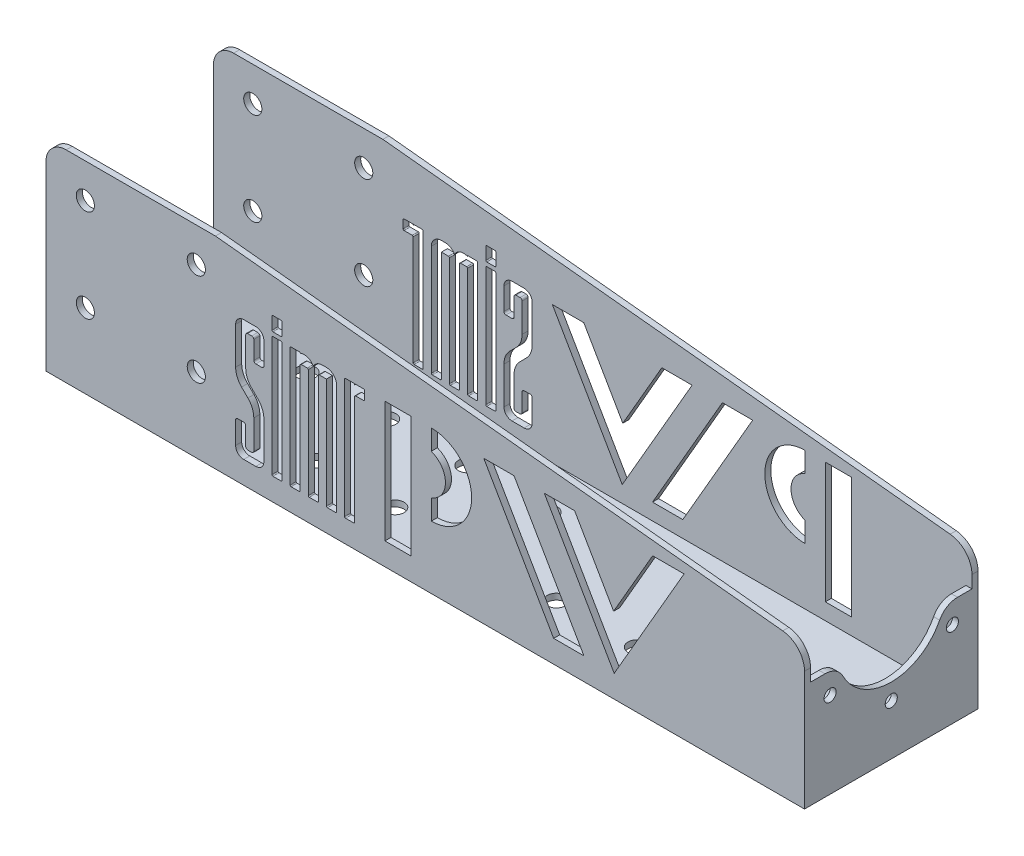
SolidWorks part; units mm, degrees
ref_plane "Płaszczyzna przednia" through (0, 0, 0) normal (0, 0, 1) x (1, 0, 0)
ref_plane "Płaszczyzna górna" through (0, 0, 0) normal (0, 1, 0) x (1, 0, 0)
ref_plane "Płaszczyzna prawa" through (0, 0, 0) normal (1, 0, 0) x (0, 0, -1)
sketch "Szkic1" plane through (0, 0, 0) normal (0, 1, 0) x (1, 0, 0)
  line L1 (-188, -43) -> (188, -43)
  line L2 (-188, -43) -> (-188, 43)
  line L3 (-188, 43) -> (188, 43)
  line L4 (188, -43) -> (188, 43)
  line L5 (-188, -43) -> (188, 43) construction
  line L6 (-188, 43) -> (188, -43) construction
  point P0 (0, 0)
  dimension "D1" = 376
  dimension "D2" = 86
extrude "Dodanie-wyciągnięcie1" add sketch "Szkic1" along normal blind 100
sketch "Szkic2" plane through (188, 0, 0) normal (1, 0, 0) x (0, 0, -1)
  line L0 (-43, 100) -> (43, 100) construction
  line L1 (-40, 100) -> (40, 100)
  line L2 (-40, 100) -> (-40, 3)
  line L3 (-40, 3) -> (40, 3)
  line L4 (40, 100) -> (40, 3)
  line L5 (-43, 100) -> (-43, 0) construction
  line L6 (43, 100) -> (43, 0) construction
  line L7 (-43, 0) -> (43, 0) construction
  dimension "D1" = 3
  dimension "D2" = 3
  dimension "D3" = 3
extrude "Wytnij-wyciągnięcie1" cut sketch "Szkic2" against normal through all
sketch "Szkic3" plane through (0, 0, 43) normal (0, 0, 1) x (1, 0, 0)
  line L0 (-104, 100) -> (188, 70)
  line L1 (-188, 100) -> (188, 100) construction
  line L3 (-188, 100) -> (-188, 0) construction
  line L4 (188, 100) -> (188, 0) construction
  line L5 (-188, 0) -> (188, 0) construction
  line M3 (188, 0) -> (188, 100)
  line M4 (188, 100) -> (-188, 100)
  dimension "D1" = 84
  dimension "D2" = 70
extrude "Wytnij-wyciągnięcie2" cut sketch "Szkic3" against normal blind 100 and the other way through all contours L0 M4 M3
fillet "Zaokrąglenie1" radius 12 2 edges at (188, 70, -41.5) (188, 70, 41.5)
fillet "Zaokrąglenie2" radius 10 2 edges at (-188, 100, -41.5) (-188, 100, 41.5)
sketch "Szkic4" plane through (0, 0, 43) normal (0, 0, 1) x (1, 0, 0)
  line L0 (-141, 100) -> (-141, -83.0403) construction
  line L1 (-178, 100) -> (-104, 100) construction
  line L2 (-188, 0) -> (188, 0) construction
  circle A0 centre (-168.5, 83) radius 4.5
  circle A1 centre (-168.5, 37) radius 4.5
  circle A2 centre (-113.5, 37) radius 4.5
  circle A3 centre (-113.5, 83) radius 4.5
  dimension "D1" = 9
  dimension "D3" = 9
  dimension "D2" = 55
  dimension "D4" = 46
  dimension "D5" = 37
extrude "Wytnij-wyciągnięcie3" cut sketch "Szkic4" against normal through all
sketch "Szkic5" plane through (0, 0, 0) normal (0, -1, 0) x (1, 0, 0)
  line L0 (-204.5938, 0) -> (234.3383, 0) construction
  line L1 (-188, -43) -> (-188, 43) construction
  circle A0 centre (-160, 18) radius 4.5
  circle A1 centre (-160, -18) radius 4.5
  circle A2 centre (-120, 18) radius 4.5
  circle A3 centre (-120, -18) radius 4.5
  circle A4 centre (-80, 18) radius 4.5
  circle A5 centre (-80, -18) radius 4.5
  circle A6 centre (-40, 18) radius 4.5
  circle A7 centre (-40, -18) radius 4.5
  circle A8 centre (0, 18) radius 4.5
  circle A9 centre (0, -18) radius 4.5
  circle A10 centre (40, 18) radius 4.5
  circle A11 centre (40, -18) radius 4.5
  circle A12 centre (80, 18) radius 4.5
  circle A13 centre (80, -18) radius 4.5
  circle A14 centre (120, 18) radius 4.5
  circle A15 centre (120, -18) radius 4.5
  circle A16 centre (160, 18) radius 4.5
  circle A17 centre (160, -18) radius 4.5
  dimension "D1" = 9
  dimension "D2" = 36
  dimension "D3" = 28
  dimension "D5" = 40
  dimension "D4" = 9
sketch "Szkic6" plane through (0, 3, 0) normal (0, 1, 0) x (1, 0, 0)
  line L0 (-188, -40) -> (188, -40) construction
  line L1 (188, 40) -> (185, 40)
  line L2 (188, 40) -> (188, -40)
  line L3 (188, -40) -> (185, -40)
  line L4 (185, 40) -> (185, -40)
  dimension "D1" = 3
extrude "Dodanie-wyciągnięcie2" add sketch "Szkic6" along normal blind 50
sketch "Szkic7" plane through (188, 0, 0) normal (1, 0, 0) x (0, 0, -1)
  line L0 (-43, 0) -> (43, 0) construction
  circle A0 centre (0, 60) radius 27
  dimension "D1" = 54
  dimension "D2" = 60
extrude "Wytnij-wyciągnięcie4" cut sketch "Szkic7" against normal through all
fillet "Zaokrąglenie3" radius 10 2 edges at (186.5, 53, 26.0768) (186.5, 53, -26.0768)
sketch "Szkic8" plane through (188, 0, 0) normal (1, 0, 0) x (0, 0, -1)
  line L1 (-43, 0) -> (43, 0) construction
  circle A1 centre (0, 25) radius 3
  circle A2 centre (-30.3109, 42.5) radius 3
  circle A6 centre (30.3109, 42.5) radius 3
  circle A7 centre (-30.3109, 77.5) radius 3 [skipped]
  circle A8 centre (30.3109, 77.5) radius 3 [skipped]
  circle A9 centre (0, 95) radius 3 [skipped]
  point P20 (0, 60)
  dimension "D1" = 60
  dimension "D3" = 6
  dimension "D2" = 25
  dimension "D4" = 6
extrude "Wytnij-wyciągnięcie5" cut sketch "Szkic8" against normal through all
sketch "Szkic9" plane through (0, 0, 43) normal (0, 0, 1) x (1, 0, 0)
  line L0 (-84, 55.1069) -> (-81, 55.1069)
  line L1 (-80, 56.1069) -> (-80, 67.1069)
  line L2 (-84, 71.1069) -> (-90, 71.1069)
  line L3 (-94, 67.1069) -> (-94, 48.7135)
  line L4 (-91.0711, 41.6424) -> (-87.9289, 38.5003)
  line L5 (-85, 31.4292) -> (-85, 17.1069)
  line L6 (-86, 16.1069) -> (-88, 16.1069)
  line L7 (-89, 17.1069) -> (-89, 26.1069)
  line L8 (-90, 27.1069) -> (-93, 27.1069)
  line L9 (-94, 26.1069) -> (-94, 15.1069)
  line L10 (-90, 11.1069) -> (-84, 11.1069)
  line L11 (-80, 15.1069) -> (-80, 33.5003)
  line L12 (-82.9289, 40.5713) -> (-86.0711, 43.7135)
  line L13 (-89, 50.7845) -> (-89, 65.1069)
  line L14 (-88, 66.1069) -> (-86, 66.1069)
  line L15 (-85, 65.1069) -> (-85, 56.1069)
  line L16 (-204.5938, 0) -> (234.3383, 0) construction
  line L17 (-133.6296, 71.1069) -> (214.4574, 71.1069) construction
  line L18 (-135.0866, 11.1069) -> (178.3378, 11.1069) construction
  line L20 (-75.5, 71.1069) -> (-71.5, 71.1069)
  line L21 (-76, 70.6069) -> (-76, 11.6069)
  line L22 (-75.5, 11.1069) -> (-71.5, 11.1069)
  line L23 (-71, 70.6069) -> (-71, 11.6069)
  line L24 (-75.5, 73.1069) -> (-71.5, 73.1069)
  line L25 (-76, 73.6069) -> (-76, 79.6069)
  line L26 (-75.5, 80.1069) -> (-71.5, 80.1069)
  line L27 (-71, 73.6069) -> (-71, 79.6069)
  line L29 (-67, 70.6069) -> (-67, 11.6069)
  line L30 (-66.5, 11.1069) -> (-62.5, 11.1069)
  line L31 (-62, 65.6069) -> (-62, 11.6069)
  line L33 (-58, 65.6069) -> (-58, 11.6069)
  line L34 (-57.5, 11.1069) -> (-53.5, 11.1069)
  line L35 (-53, 65.6069) -> (-53, 11.6069)
  line L37 (-49, 66.1069) -> (-49, 11.6069)
  line L38 (-48.5, 11.1069) -> (-44.5, 11.1069)
  line L39 (-44, 66.1069) -> (-44, 11.6069)
  line L42 (-61.5, 66.1069) -> (-58.5, 66.1069)
  line L44 (-52.5, 66.1069) -> (-49, 66.1069)
  line L48 (-66.5, 71.1069) -> (-62, 71.1069)
  line L49 (-62, 70.6895) -> (-62, 71.1069)
  line L50 (-30, 70.6069) -> (-30, 66.6069)
  line L51 (-39.5, 11.1069) -> (-35.5, 11.1069)
  line L52 (-40, 11.6069) -> (-40, 70.6069)
  line L53 (-39.5, 71.1069) -> (-35, 71.1069)
  line L54 (-35, 11.6069) -> (-35, 65.6069)
  line L55 (-30.5, 66.1069) -> (-34.5, 66.1069)
  line L58 (3, 41.1069) -> (3, 31.1069)
  line L59 (-34.5, 71.1069) -> (-30.5, 71.1069)
  line L60 (-35, 70.6069) -> (-35, 71.1069)
  line L61 (-51, 71.1069) -> (-49, 71.1069)
  line L62 (-20, 71.1069) -> (-7, 71.1069)
  line L63 (-20, 71.1069) -> (-20, 11.1069)
  line L64 (-20, 11.1069) -> (-7, 11.1069)
  line L65 (-7, 71.1069) -> (-7, 11.1069)
  line L66 (3, 61.1069) -> (3, 71.1069)
  line L67 (29, 71.1069) -> (63.641, 11.1069)
  line L68 (63.641, 11.1069) -> (78.6521, 11.1069)
  line L69 (78.6521, 11.1069) -> (44.0111, 71.1069)
  line L70 (44.0111, 71.1069) -> (29, 71.1069)
  line L71 (59.0222, 71.1069) -> (93.6632, 11.1069)
  line L72 (93.6632, 11.1069) -> (128.3042, 71.1069)
  line L73 (128.3042, 71.1069) -> (112.7158, 71.1069)
  line L74 (112.7158, 71.1069) -> (93.3746, 37.6069)
  line L75 (93.3746, 37.6069) -> (74.0333, 71.1069)
  line L76 (74.0333, 71.1069) -> (59.0222, 71.1069)
  arc A0 (-94, 48.7135) -> (-91.0711, 41.6424) centre (-84, 48.7135) ccw
  arc A1 (-87.9289, 38.5003) -> (-85, 31.4292) centre (-95, 31.4292) cw
  arc A2 (-80, 33.5003) -> (-82.9289, 40.5713) centre (-90, 33.5003) ccw
  arc A3 (-86.0711, 43.7135) -> (-89, 50.7845) centre (-79, 50.7845) cw
  arc A4 (-84, 11.1069) -> (-80, 15.1069) centre (-84, 15.1069) ccw
  arc A5 (-94, 15.1069) -> (-90, 11.1069) centre (-90, 15.1069) ccw
  arc A6 (-90, 71.1069) -> (-94, 67.1069) centre (-90, 67.1069) ccw
  arc A7 (-80, 67.1069) -> (-84, 71.1069) centre (-84, 67.1069) ccw
  arc A8 (-49, 71.1069) -> (-44, 66.1069) centre (-49, 66.1069) cw
  arc A9 (-51, 71.1069) -> (-55.5, 68.2863) centre (-51, 66.1069) ccw
  arc A10 (-60, 71.1069) -> (-55.5, 68.2863) centre (-60, 66.1069) cw
  arc A11 (-60, 71.1069) -> (-62, 70.6895) centre (-60, 66.1069) ccw
  arc A13 (-81, 55.1069) -> (-80, 56.1069) centre (-81, 56.1069) ccw
  arc A14 (-84, 55.1069) -> (-85, 56.1069) centre (-84, 56.1069) cw
  arc A15 (-93, 27.1069) -> (-94, 26.1069) centre (-93, 26.1069) ccw
  arc A16 (-89, 26.1069) -> (-90, 27.1069) centre (-90, 26.1069) ccw
  arc A17 (-85, 17.1069) -> (-86, 16.1069) centre (-86, 17.1069) cw
  arc A18 (-88, 16.1069) -> (-89, 17.1069) centre (-88, 17.1069) cw
  arc A19 (-89, 65.1069) -> (-88, 66.1069) centre (-88, 65.1069) cw
  arc A20 (-86, 66.1069) -> (-85, 65.1069) centre (-86, 65.1069) cw
  arc A22 (-40, 70.6069) -> (-39.5, 71.1069) centre (-39.5, 70.6069) cw
  arc A23 (-34.5, 66.1069) -> (-35, 65.6069) centre (-34.5, 65.6069) ccw
  arc A24 (-30, 66.6069) -> (-30.5, 66.1069) centre (-30.5, 66.6069) cw
  arc A25 (-30, 70.6069) -> (-30.5, 71.1069) centre (-30.5, 70.6069) ccw
  arc A26 (-35.5, 11.1069) -> (-35, 11.6069) centre (-35.5, 11.6069) ccw
  arc A27 (-39.5, 11.1069) -> (-40, 11.6069) centre (-39.5, 11.6069) cw
  arc A28 (-67, 11.6069) -> (-66.5, 11.1069) centre (-66.5, 11.6069) ccw
  arc A29 (-62.5, 11.1069) -> (-62, 11.6069) centre (-62.5, 11.6069) ccw
  arc A30 (-58, 11.6069) -> (-57.5, 11.1069) centre (-57.5, 11.6069) ccw
  arc A31 (-53.5, 11.1069) -> (-53, 11.6069) centre (-53.5, 11.6069) ccw
  arc A32 (-49, 11.6069) -> (-48.5, 11.1069) centre (-48.5, 11.6069) ccw
  arc A33 (-44.5, 11.1069) -> (-44, 11.6069) centre (-44.5, 11.6069) ccw
  arc A34 (-52.5, 66.1069) -> (-53, 65.6069) centre (-52.5, 65.6069) ccw
  arc A35 (-62, 65.6069) -> (-61.5, 66.1069) centre (-61.5, 65.6069) cw
  arc A36 (-58.5, 66.1069) -> (-58, 65.6069) centre (-58.5, 65.6069) cw
  arc A37 (-66.5, 71.1069) -> (-67, 70.6069) centre (-66.5, 70.6069) ccw
  arc A38 (-76, 79.6069) -> (-75.5, 80.1069) centre (-75.5, 79.6069) cw
  arc A39 (-71.5, 80.1069) -> (-71, 79.6069) centre (-71.5, 79.6069) cw
  arc A40 (-71.5, 73.1069) -> (-71, 73.6069) centre (-71.5, 73.6069) ccw
  arc A41 (-75.5, 73.1069) -> (-76, 73.6069) centre (-75.5, 73.6069) cw
  arc A42 (-75.5, 71.1069) -> (-76, 70.6069) centre (-75.5, 70.6069) ccw
  arc A43 (-71.5, 71.1069) -> (-71, 70.6069) centre (-71.5, 70.6069) cw
  arc A44 (-71.5, 11.1069) -> (-71, 11.6069) centre (-71.5, 11.6069) ccw
  arc A45 (-76, 11.6069) -> (-75.5, 11.1069) centre (-75.5, 11.6069) ccw
  arc A46 (-34.5, 71.1069) -> (-35, 70.6069) centre (-34.5, 70.6069) ccw
  arc A47 (3, 71.1069) -> (3, 31.1069) centre (3, 51.1069) cw
  arc A50 (3, 61.1069) -> (3, 41.1069) centre (-0.6429, 51.1069) cw
  point P5 (-87, 11.1069)
  point P55 (-60, 66.1069)
  point P71 (-55.5, 11.1069)
  point P89 (-89, 27.1069)
  point P92 (-85, 16.1069)
  point P95 (-89, 16.1069)
  point P110 (-35, 66.1069)
  point P120 (-40, 11.1069)
  point P125 (-62, 11.1069)
  point P130 (-53, 11.1069)
  point P135 (-44, 11.1069)
  point P144 (-67, 71.1069)
  point P147 (-76, 80.1069)
  point P150 (-71, 80.1069)
  point P153 (-71, 73.1069)
  point P158 (-76, 71.1069)
  point P163 (-71, 11.1069)
  point P172 (-7, 41.1069)
  dimension "D11" = 10
  dimension "D12" = 4
  dimension "D25" = 5
  dimension "D31" = 1
  dimension "D32" = 0.5
  dimension "D33" = 0.5
  dimension "D37" = 13
  dimension "D36" = 10
  dimension "D1" = 5
  dimension "D2" = 5
  dimension "D3" = 5
  dimension "D4" = 5
  dimension "D5" = 5
  dimension "D6" = 5
  dimension "D7" = 5
  dimension "D8" = 60
  dimension "D9" = 135
  dimension "D10" = 4
  dimension "D13" = 11
  dimension "D14" = 5
  dimension "D15" = 4
  dimension "D16" = 7
  dimension "D17" = 5
  dimension "D18" = 2
  dimension "D19" = 5
  dimension "D20" = 4
  dimension "D21" = 5
  dimension "D22" = 4
  dimension "D23" = 5
  dimension "D24" = 5
  dimension "D26" = 5
  dimension "D27" = 5
  dimension "D28" = 4
  dimension "D29" = 5
  dimension "D30" = 5
  dimension "D34" = 4
  dimension "D35" = 13
  dimension "D38" = 10
  dimension "D39" = 60
  dimension "D40" = 60
  dimension "D41" = 13
  dimension "D42" = 13.5
  dimension "D43" = 13
  dimension "D44" = 13
  dimension "D45" = 10
  dimension "D46" = 26
  dimension "D47" = 10
extrude "Wytnij-wyciągnięcie6" cut sketch "Szkic9" against normal up to next
sketch "Szkic11" plane through (0, 0, -43) normal (0, 0, -1) x (-1, 0, 0)
  line L0 (40, 55.1069) -> (43, 55.1069)
  line L1 (44, 56.1069) -> (44, 67.1069)
  line L2 (40, 71.1069) -> (34, 71.1069)
  line L3 (30, 67.1069) -> (30, 48.7135)
  line L4 (32.9289, 41.6424) -> (36.0711, 38.5003)
  line L5 (39, 31.4292) -> (39, 17.1069)
  line L6 (38, 16.1069) -> (36, 16.1069)
  line L7 (35, 17.1069) -> (35, 26.1069)
  line L8 (34, 27.1069) -> (31, 27.1069)
  line L9 (30, 26.1069) -> (30, 15.1069)
  line L10 (34, 11.1069) -> (40, 11.1069)
  line L11 (44, 15.1069) -> (44, 33.5003)
  line L12 (41.0711, 40.5713) -> (37.9289, 43.7135)
  line L13 (35, 50.7845) -> (35, 65.1069)
  line L14 (36, 66.1069) -> (38, 66.1069)
  line L15 (39, 65.1069) -> (39, 56.1069)
  line L16 (-236.0463, 71.1069) -> (188, 71.1069) construction
  line L17 (-237.8027, 11.1069) -> (188, 11.1069) construction
  line L18 (48.5, 71.1069) -> (52.5, 71.1069)
  line L19 (48, 70.6069) -> (48, 11.6069)
  line L20 (48.5, 11.1069) -> (52.5, 11.1069)
  line L21 (53, 70.6069) -> (53, 11.6069)
  line L22 (48.5, 73.1069) -> (52.5, 73.1069)
  line L23 (48, 73.6069) -> (48, 79.6069)
  line L24 (48.5, 80.1069) -> (52.5, 80.1069)
  line L25 (53, 73.6069) -> (53, 79.6069)
  line L26 (57, 70.6069) -> (57, 11.6069)
  line L27 (57.5, 11.1069) -> (61.5, 11.1069)
  line L28 (62, 65.6069) -> (62, 11.6069)
  line L29 (66, 65.6069) -> (66, 11.6069)
  line L30 (66.5, 11.1069) -> (70.5, 11.1069)
  line L31 (71, 65.6069) -> (71, 11.6069)
  line L32 (75, 66.1069) -> (75, 11.6069)
  line L33 (75.5, 11.1069) -> (79.5, 11.1069)
  line L34 (80, 66.1069) -> (80, 11.6069)
  line L35 (62.5, 66.1069) -> (65.5, 66.1069)
  line L36 (71.5, 66.1069) -> (75, 66.1069)
  line L37 (57.5, 71.1069) -> (62, 71.1069)
  line L38 (62, 70.6895) -> (62, 71.1069)
  line L39 (94, 70.6069) -> (94, 66.6069)
  line L40 (84.5, 11.1069) -> (88.5, 11.1069)
  line L41 (84, 11.6069) -> (84, 70.6069)
  line L42 (84.5, 71.1069) -> (89, 71.1069)
  line L43 (89, 11.6069) -> (89, 65.6069)
  line L44 (93.5, 66.1069) -> (89.5, 66.1069)
  line L46 (89.5, 71.1069) -> (93.5, 71.1069)
  line L47 (89, 70.6069) -> (89, 71.1069)
  line L48 (73, 71.1069) -> (75, 71.1069)
  line L64 (-105.3042, 41.1069) -> (-105.3042, 31.1069)
  line L65 (-128.3042, 71.1069) -> (-115.3042, 71.1069)
  line L66 (-128.3042, 71.1069) -> (-128.3042, 11.1069)
  line L67 (-128.3042, 11.1069) -> (-115.3042, 11.1069)
  line L68 (-115.3042, 71.1069) -> (-115.3042, 11.1069)
  line L69 (-105.3042, 61.1069) -> (-105.3042, 71.1069)
  line L70 (-79.3042, 71.1069) -> (-44.6632, 11.1069)
  line L71 (-44.6632, 11.1069) -> (-29.6521, 11.1069)
  line L72 (-29.6521, 11.1069) -> (-64.2931, 71.1069)
  line L73 (-64.2931, 71.1069) -> (-79.3042, 71.1069)
  line L74 (-49.282, 71.1069) -> (-14.641, 11.1069)
  line L75 (-14.641, 11.1069) -> (20, 71.1069)
  line L76 (20, 71.1069) -> (4.4115, 71.1069)
  line L77 (4.4115, 71.1069) -> (-14.9297, 37.6069)
  line L78 (-14.9297, 37.6069) -> (-34.2709, 71.1069)
  line L79 (-34.2709, 71.1069) -> (-49.282, 71.1069)
  line L80 (188, 90) -> (188, 0) construction
  arc A0 (30, 48.7135) -> (32.9289, 41.6424) centre (40, 48.7135) ccw
  arc A1 (36.0711, 38.5003) -> (39, 31.4292) centre (29, 31.4292) cw
  arc A2 (44, 33.5003) -> (41.0711, 40.5713) centre (34, 33.5003) ccw
  arc A3 (37.9289, 43.7135) -> (35, 50.7845) centre (45, 50.7845) cw
  arc A4 (40, 11.1069) -> (44, 15.1069) centre (40, 15.1069) ccw
  arc A5 (30, 15.1069) -> (34, 11.1069) centre (34, 15.1069) ccw
  arc A6 (34, 71.1069) -> (30, 67.1069) centre (34, 67.1069) ccw
  arc A7 (44, 67.1069) -> (40, 71.1069) centre (40, 67.1069) ccw
  arc A8 (75, 71.1069) -> (80, 66.1069) centre (75, 66.1069) cw
  arc A9 (73, 71.1069) -> (68.5, 68.2863) centre (73, 66.1069) ccw
  arc A10 (64, 71.1069) -> (68.5, 68.2863) centre (64, 66.1069) cw
  arc A11 (64, 71.1069) -> (62, 70.6895) centre (64, 66.1069) ccw
  arc A12 (43, 55.1069) -> (44, 56.1069) centre (43, 56.1069) ccw
  arc A13 (40, 55.1069) -> (39, 56.1069) centre (40, 56.1069) cw
  arc A14 (31, 27.1069) -> (30, 26.1069) centre (31, 26.1069) ccw
  arc A15 (35, 26.1069) -> (34, 27.1069) centre (34, 26.1069) ccw
  arc A16 (39, 17.1069) -> (38, 16.1069) centre (38, 17.1069) cw
  arc A17 (36, 16.1069) -> (35, 17.1069) centre (36, 17.1069) cw
  arc A18 (35, 65.1069) -> (36, 66.1069) centre (36, 65.1069) cw
  arc A19 (38, 66.1069) -> (39, 65.1069) centre (38, 65.1069) cw
  arc A20 (84, 70.6069) -> (84.5, 71.1069) centre (84.5, 70.6069) cw
  arc A21 (89.5, 66.1069) -> (89, 65.6069) centre (89.5, 65.6069) ccw
  arc A22 (94, 66.6069) -> (93.5, 66.1069) centre (93.5, 66.6069) cw
  arc A23 (94, 70.6069) -> (93.5, 71.1069) centre (93.5, 70.6069) ccw
  arc A24 (88.5, 11.1069) -> (89, 11.6069) centre (88.5, 11.6069) ccw
  arc A25 (84.5, 11.1069) -> (84, 11.6069) centre (84.5, 11.6069) cw
  arc A26 (57, 11.6069) -> (57.5, 11.1069) centre (57.5, 11.6069) ccw
  arc A27 (61.5, 11.1069) -> (62, 11.6069) centre (61.5, 11.6069) ccw
  arc A28 (66, 11.6069) -> (66.5, 11.1069) centre (66.5, 11.6069) ccw
  arc A29 (70.5, 11.1069) -> (71, 11.6069) centre (70.5, 11.6069) ccw
  arc A30 (75, 11.6069) -> (75.5, 11.1069) centre (75.5, 11.6069) ccw
  arc A31 (79.5, 11.1069) -> (80, 11.6069) centre (79.5, 11.6069) ccw
  arc A32 (71.5, 66.1069) -> (71, 65.6069) centre (71.5, 65.6069) ccw
  arc A33 (62, 65.6069) -> (62.5, 66.1069) centre (62.5, 65.6069) cw
  arc A34 (65.5, 66.1069) -> (66, 65.6069) centre (65.5, 65.6069) cw
  arc A35 (57.5, 71.1069) -> (57, 70.6069) centre (57.5, 70.6069) ccw
  arc A36 (48, 79.6069) -> (48.5, 80.1069) centre (48.5, 79.6069) cw
  arc A37 (52.5, 80.1069) -> (53, 79.6069) centre (52.5, 79.6069) cw
  arc A38 (52.5, 73.1069) -> (53, 73.6069) centre (52.5, 73.6069) ccw
  arc A39 (48.5, 73.1069) -> (48, 73.6069) centre (48.5, 73.6069) cw
  arc A40 (48.5, 71.1069) -> (48, 70.6069) centre (48.5, 70.6069) ccw
  arc A41 (52.5, 71.1069) -> (53, 70.6069) centre (52.5, 70.6069) cw
  arc A42 (52.5, 11.1069) -> (53, 11.6069) centre (52.5, 11.6069) ccw
  arc A43 (48, 11.6069) -> (48.5, 11.1069) centre (48.5, 11.6069) ccw
  arc A44 (89.5, 71.1069) -> (89, 70.6069) centre (89.5, 70.6069) ccw
  arc A47 (-105.3042, 71.1069) -> (-105.3042, 31.1069) centre (-105.3042, 51.1069) cw
  arc A48 (-105.3042, 61.1069) -> (-105.3042, 41.1069) centre (-108.9471, 51.1069) cw
  point P53 (64, 66.1069)
  point P69 (68.5, 11.1069)
  point P154 (-115.3042, 41.1069)
  dimension "D8" = 10
  dimension "D9" = 4
  dimension "D16" = 5
  dimension "D21" = 1
  dimension "D22" = 0.5
  dimension "D24" = 0.5
  dimension "D42" = 5
  dimension "D28" = 10
  dimension "D1" = 5
  dimension "D2" = 5
  dimension "D3" = 5
  dimension "D4" = 5
  dimension "D5" = 5
  dimension "D6" = 5
  dimension "D7" = 5
  dimension "D10" = 2
  dimension "D11" = 5
  dimension "D12" = 4
  dimension "D13" = 5
  dimension "D14" = 4
  dimension "D15" = 5
  dimension "D17" = 5
  dimension "D18" = 5
  dimension "D19" = 4
  dimension "D20" = 5
  dimension "D23" = 5
  dimension "D25" = 5
  dimension "D26" = 10
  dimension "D27" = 13
  dimension "D29" = 13
  dimension "D30" = 13
  dimension "D31" = 13.5
  dimension "D32" = 13
  dimension "D33" = 26
  dimension "D34" = 13
  dimension "D35" = 60
  dimension "D36" = 4
  dimension "D37" = 4
  dimension "D38" = 4
  dimension "D39" = 7
  dimension "D40" = 5
  dimension "D41" = 11
  dimension "D43" = 18.3934
  dimension "D44" = 60
  dimension "D45" = 10
  dimension "D46" = 60
  dimension "D47" = 60
  dimension "D48" = 10
extrude "Wytnij-wyciągnięcie7" cut sketch "Szkic11" against normal up to next
extrude "Wytnij-wyciągnięcie8" cut sketch "Szkic5" against normal through all
